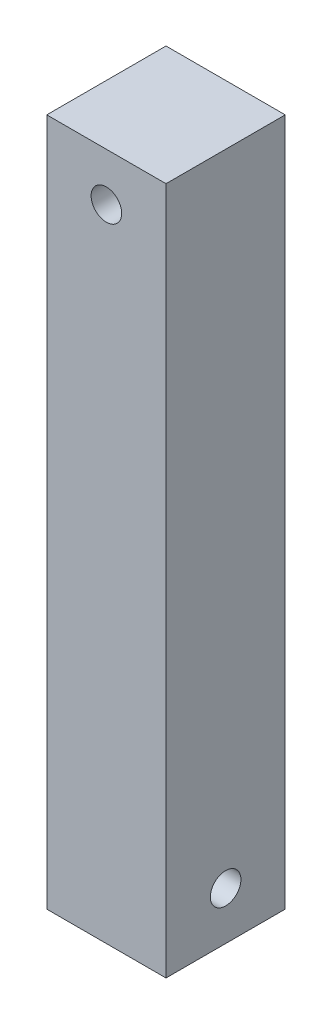
SolidWorks part; units mm, degrees
ref_plane "Front Plane" through (0, 0, 0) normal (0, 0, 1) x (1, 0, 0)
ref_plane "Top Plane" through (0, 0, 0) normal (0, 1, 0) x (1, 0, 0)
ref_plane "Right Plane" through (0, 0, 0) normal (1, 0, 0) x (0, 0, -1)
sketch "Sketch1" plane through (0, 0, 0) normal (0, 1, 0) x (1, 0, 0)
  line L1 (-5.85, 5.85) -> (5.85, 5.85)
  line L2 (-5.85, 5.85) -> (-5.85, -5.85)
  line L3 (-5.85, -5.85) -> (5.85, -5.85)
  line L4 (5.85, 5.85) -> (5.85, -5.85)
  line L5 (-5.85, 5.85) -> (5.85, -5.85) construction
  line L6 (-5.85, -5.85) -> (5.85, 5.85) construction
  point P0 (0, 0)
  dimension "D1" = 11.7
extrude "Boss-Extrude1" add sketch "Sketch1" along normal blind 67.5
sketch "Sketch2" plane through (0, 0, 5.85) normal (0, 0, 1) x (1, 0, 0)
  line L0 (-5.85, 67.5) -> (5.85, 67.5) construction
  circle A0 centre (0, 62.8) radius 1.5
  point P4 (0, 67.5)
  dimension "D1" = 3
  dimension "D2" = 4.7
extrude "Cut-Extrude1" cut sketch "Sketch2" against normal through all
sketch "Sketch5" plane through (0, 0, -5.85) normal (0, 0, -1) x (-1, 0, 0)
  line L0 (-2.2111, 17.5772) -> (0.5686, 17.5772)
  line L1 (-2.2111, 17.5772) -> (-2.2111, 14.4184)
  line L2 (0.5686, 17.5772) -> (0.5686, 14.4184)
  line L3 (-2.2111, 14.4184) -> (0.5686, 14.4184)
extrude "Cut-Extrude4" cut sketch "Sketch5" against normal blind 10
sketch "Sketch6" plane through (5.85, 0, 0) normal (1, 0, 0) x (0, 0, -1)
  line L0 (-5.85, 0) -> (5.85, 0) construction
  line L1 (5.85, 67.5) -> (5.85, 0) construction
  circle A0 centre (0, 4.7) radius 1.5
  dimension "D1" = 3
  dimension "D2" = 4.7
  dimension "D3" = 5.85
extrude "Cut-Extrude5" cut sketch "Sketch6" against normal through all
